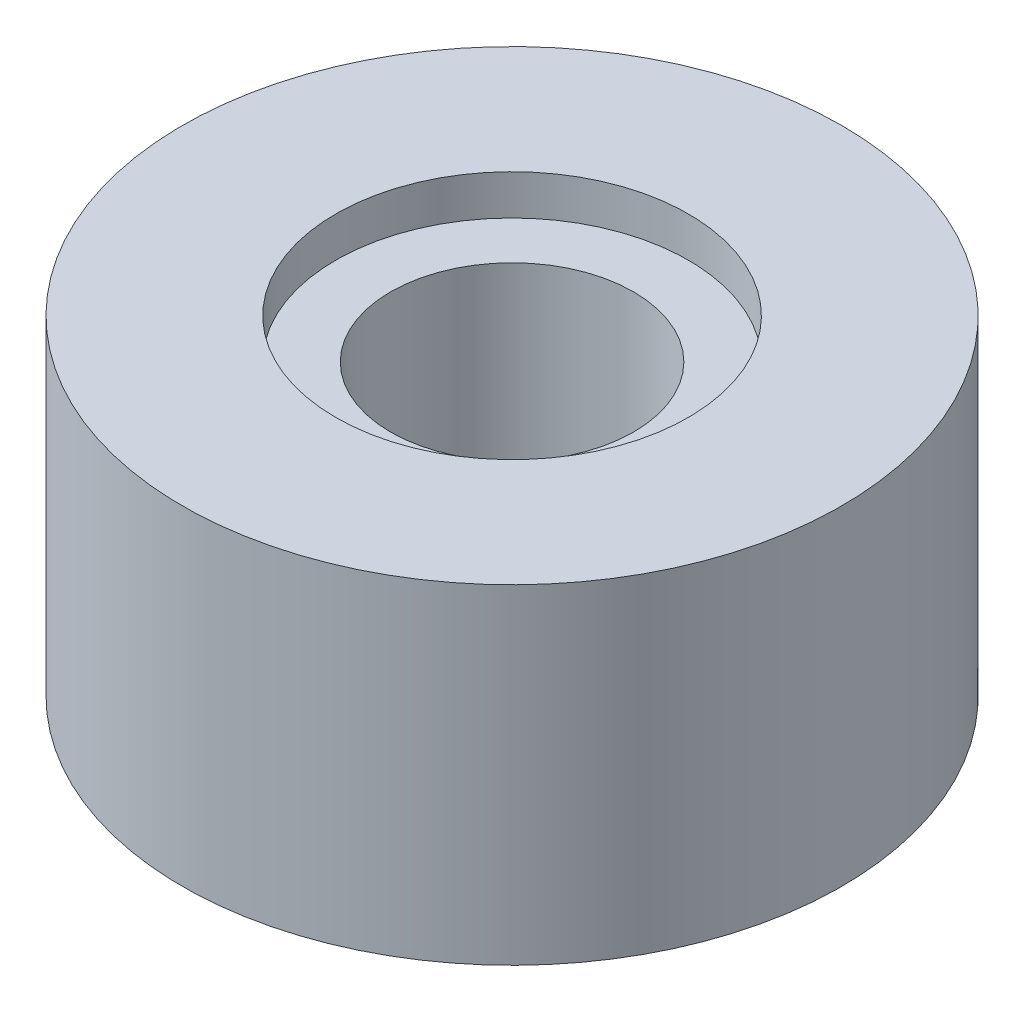
SolidWorks part; units mm, degrees
ref_plane "Front Plane" through (0, 0, 0) normal (0, 0, 1) x (1, 0, 0)
ref_plane "Top Plane" through (0, 0, 0) normal (0, 1, 0) x (1, 0, 0)
ref_plane "Right Plane" through (0, 0, 0) normal (1, 0, 0) x (0, 0, -1)
sketch "Sketch1" plane through (0, 0, 0) normal (0, 1, 0) x (1, 0, 0)
  circle A0 centre (0, 0) radius 38.1
  dimension "D1" = 76.2
extrude "Boss-Extrude1" add sketch "Sketch1" along normal blind 38.1
sketch "Sketch2" plane through (0, 0, 0) normal (0, -1, 0) x (1, 0, 0)
  circle A0 centre (0, 0) radius 14.0462
  dimension "D1" = 28.0924
extrude "Cut-Extrude1" cut sketch "Sketch2" against normal blind 76.2
sketch "Sketch3" plane through (0, 38.1, 0) normal (0, 1, 0) x (1, 0, 0)
  circle A0 centre (0, 0) radius 20.3835
  dimension "D1" = 40.767
extrude "Cut-Extrude2" cut sketch "Sketch3" against normal blind 4.633
sketch "Sketch4" plane through (0, 0, 0) normal (0, -1, 0) x (1, 0, 0)
  circle A0 centre (0, 0) radius 30.0355
  dimension "D1" = 60.071
extrude "Cut-Extrude3" cut sketch "Sketch4" against normal blind 12.7
